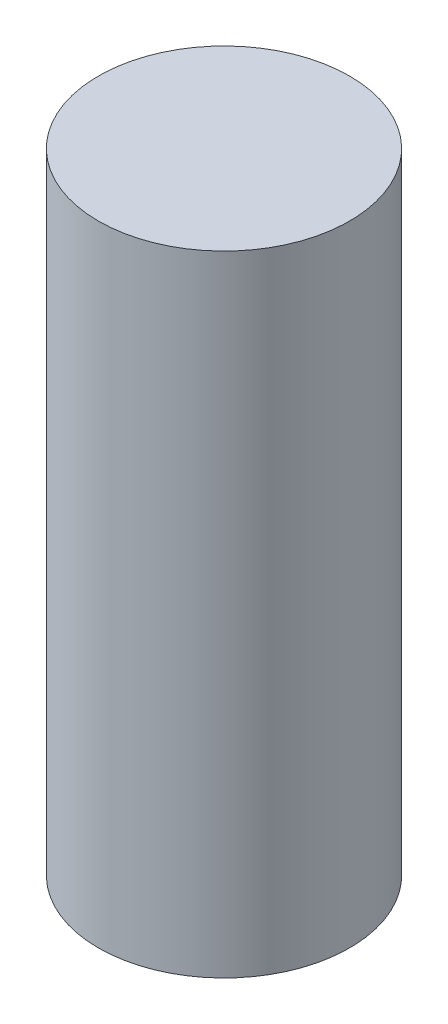
SolidWorks part; units mm, degrees
ref_plane "Front Plane" through (0, 0, 0) normal (0, 0, 1) x (1, 0, 0)
ref_plane "Top Plane" through (0, 0, 0) normal (0, 1, 0) x (1, 0, 0)
ref_plane "Right Plane" through (0, 0, 0) normal (1, 0, 0) x (0, 0, -1)
sketch "Sketch1" plane through (0, 0, 0) normal (0, 1, 0) x (1, 0, 0)
  circle A0 centre (0, 0) radius 13
  dimension "D1" = 26
extrude "Boss-Extrude1" add sketch "Sketch1" along normal blind 65.15
ref_plane "Plane1" through (0, 32.575, 0) normal (0, 1, 0) x (1, 0, 0)
